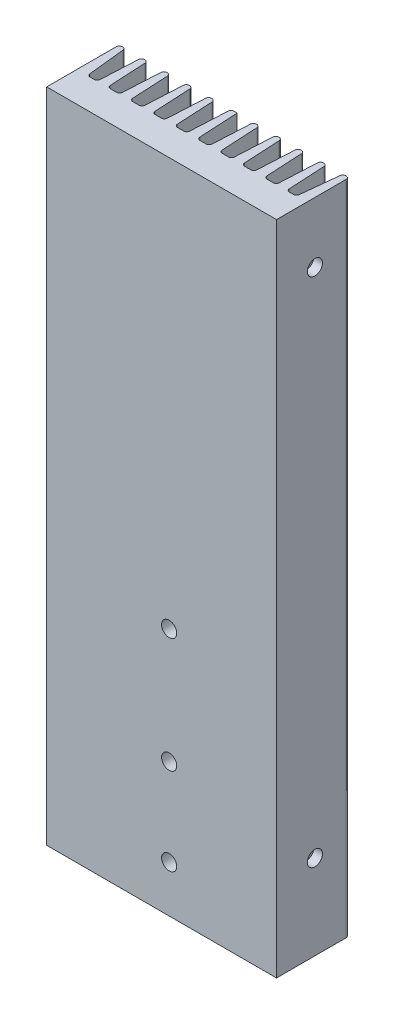
SolidWorks part; units mm, degrees
ref_plane "Front Plane" through (0, 0, 0) normal (0, 0, 1) x (1, 0, 0)
ref_plane "Top Plane" through (0, 0, 0) normal (0, 1, 0) x (1, 0, 0)
ref_plane "Right Plane" through (0, 0, 0) normal (1, 0, 0) x (0, 0, -1)
sketch "Sketch1" plane through (0, 0, 0) normal (0, 1, 0) x (1, 0, 0)
  line L0 (0, 12) -> (0, 0)
  line L1 (0, 0) -> (38, 0)
  line L3 (0, 12) -> (1, 12)
  line L4 (1, 12) -> (1.7357, 5)
  line L26 (1.7357, 5) -> (36.2643, 5)
  line L32 (37, 12) -> (38, 12)
  line L41 (38, 0) -> (38, 12)
  line L42 (36.2643, 5) -> (37, 12)
  dimension "D1" = 38
  dimension "D2" = 12
  dimension "D3" = 6
  dimension "D7" = 6
  dimension "D21" = 1
extrude "Extrude1" add sketch "Sketch1" along normal blind 108.6
sketch "Sketch3" plane through (0, 108.6, 0) normal (0, 1, 0) x (1, 0, 0)
  line L0 (3.3331, 5) -> (3.7, 12)
  line L1 (3.7, 12) -> (4.7, 12)
  line L2 (4.7, 12) -> (5.0669, 5)
  line L3 (3.3331, 5) -> (5.0669, 5)
  line L4 (4.2, 12) -> (4.2, -2.4726) construction
  line L5 (0, 12) -> (0, 0) construction
  dimension "D1" = 4.2
  dimension "D2" = 1
extrude "Boss-Extrude1" add sketch "Sketch3" against normal up to surface (108.6 mm away) up to face at (19, 0, -7.25)
pattern_linear "LPattern1" count 9 spacing 3.7 along (1, 0, 0) of "Boss-Extrude1"
fillet "Fillet1" radius 0.5 20 edges at (36.2643, 54.3, -5) (30.9669, 54.3, -5) (29.2331, 54.3, -5) (27.2669, 54.3, -5) (25.5331, 54.3, -5) (23.5669, 54.3, -5) (21.8331, 54.3, -5) (19.8669, 54.3, -5) (18.1331, 54.3, -5) (16.1669, 54.3, -5) (14.4331, 54.3, -5) (12.4669, 54.3, -5) (10.7331, 54.3, -5) (8.7669, 54.3, -5) (7.0331, 54.3, -5) (1.7357, 54.3, -5) (5.0669, 54.3, -5) (3.3331, 54.3, -5) (34.6669, 54.3, -5) (32.9331, 54.3, -5)
fillet "Fillet2" radius 0.5 21 edges at (38, 54.3, -12) (37, 54.3, -12) (34.3, 54.3, -12) (33.3, 54.3, -12) (30.6, 54.3, -12) (29.6, 54.3, -12) (26.9, 54.3, -12) (25.9, 54.3, -12) (23.2, 54.3, -12) (22.2, 54.3, -12) (18.5, 54.3, -12) (15.8, 54.3, -12) (14.8, 54.3, -12) (12.1, 54.3, -12) (11.1, 54.3, -12) (8.4, 54.3, -12) (7.4, 54.3, -12) (4.7, 54.3, -12) (3.7, 54.3, -12) (1, 54.3, -12) (0, 54.3, -12)
sketch "Sketch5" plane through (38, 0, 0) normal (1, 0, 0) x (0, 0, -1)
  line L0 (0, 108.6) -> (0, 0) construction
  line L1 (5.4477, 108.6) -> (11.5523, 108.6) construction
  line L2 (0, 0) -> (11.5, 0) construction
  circle A0 centre (6.35, 98.6) radius 2.1
  circle A1 centre (6.35, 10) radius 2.1
  point P4 (8.5, 108.6)
  dimension "D1" = 6.35
  dimension "D2" = 10
  dimension "D3" = 4.2
  dimension "D4" = 10
  dimension "D6" = 4.2
  dimension "D5" = 6.35
extrude "Cut-Extrude1" [suppressed] cut sketch "Sketch5" against normal blind 2.5
hole_wizard "M3x0.5 Tapped Hole1" positions "Sketch7" profile "Sketch6" tap size "M3x0.5" standard "Ansi Metric"
sketch "Sketch7" plane through (38, 0, 0) normal (1, 0, 0) x (0, 0, -1)
  line L0 (0, 108.6) -> (0, 0) construction
  line L1 (0, 108.6) -> (11.5, 108.6) construction
  point P0 (6.35, 98.6)
  point P6 (6.35, 14)
  dimension "D1" = 6.35
  dimension "D2" = 10
  dimension "D3" = 6.35
  dimension "D4" = 84.6
sketch "Sketch6" plane through (38, 98.6, -6.35) normal (0, 1, 0) x (0, 0, -1)
  line L0 (0, 0) -> (0, 7.2511)
  line L1 (0, 7.2511) -> (1.25, 6.5)
  line L2 (1.25, 6.5) -> (1.25, 0)
  line L5 (1.25, 0) -> (0, 0)
  line L10 (0, 7.2511) -> (-1.25, 6.5) construction
  line L11 (0, -6.35) -> (0, 107.95) construction
  dimension "Tap Drill Dia." = 2.5
  dimension "Tap Drill Depth" = 6.5
  dimension "Drill Angle" = 118
cosmetic thread "Hole Thread1" parameters "D1"=5, "D2"=3
cosmetic thread "Hole Thread2" parameters "D1"=5, "D2"=3
hole_wizard "M3x0.5 Tapped Hole2" positions "Sketch9" profile "Sketch8" tap size "M3x0.5" standard "Ansi Metric"
sketch "Sketch9" plane through (0, 0, 0) normal (0, 0, 1) x (1, 0, 0)
  line L0 (38, 108.6) -> (38, 0) construction
  line L3 (0, 0) -> (38, 0) construction
  point P0 (20.25, 41.11)
  point P1 (20.25, 22.11)
  point P3 (20.25, 7.71)
  dimension "D1" = 17.75
  dimension "D2" = 17.75
  dimension "D3" = 17.75
  dimension "D4" = 7.71
  dimension "D5" = 22.11
  dimension "D6" = 41.11
sketch "Sketch8" plane through (20.25, 41.11, 0) normal (1, 0, 0) x (0, -1, 0)
  line L0 (0, 0) -> (0, 5.7511)
  line L1 (0, 5.7511) -> (1.25, 5)
  line L2 (1.25, 5) -> (1.25, 0)
  line L5 (1.25, 0) -> (0, 0)
  line L10 (0, 5.7511) -> (-1.25, 5) construction
  line L11 (0, -6.35) -> (0, 107.95) construction
  dimension "Tap Drill Dia." = 2.5
  dimension "Tap Drill Depth" = 5
  dimension "Drill Angle" = 118
cosmetic thread "Hole Thread3" parameters "D1"=5, "D2"=3
cosmetic thread "Hole Thread4" parameters "D1"=5, "D2"=3
cosmetic thread "Hole Thread5" parameters "D1"=5, "D2"=3
